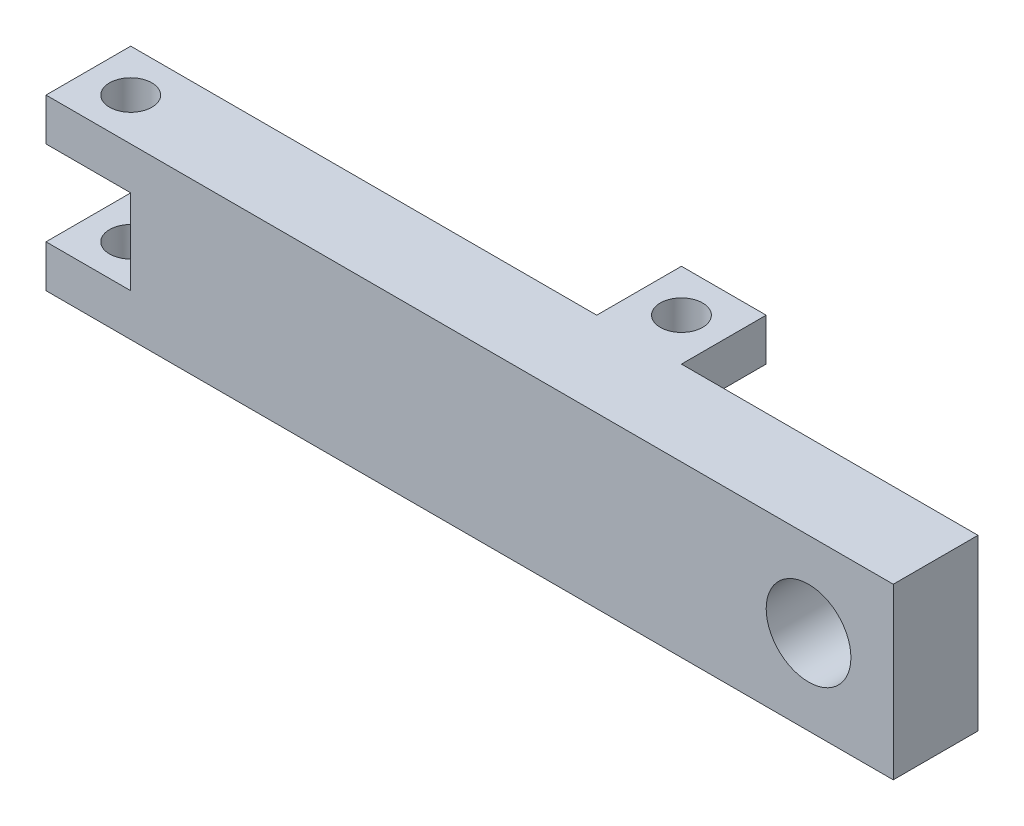
SolidWorks part; units mm, degrees
ref_plane "Front" through (0, 0, 0) normal (0, 0, 1) x (1, 0, 0)
ref_plane "Top" through (0, 0, 0) normal (0, 1, 0) x (1, 0, 0)
ref_plane "Right" through (0, 0, 0) normal (1, 0, 0) x (0, 0, -1)
sketch "Sketch1" plane through (0, 0, 0) normal (0, 1, 0) x (1, 0, 0)
  line L1 (-60, 5) -> (40, 5)
  line L2 (-60, 5) -> (-60, -5)
  line L3 (-60, -5) -> (40, -5)
  line L4 (40, 5) -> (40, -5)
  line L5 (-60, 5) -> (40, -5) construction
  line L6 (-60, -5) -> (40, 5) construction
  line L8 (-5, 15) -> (5, 15)
  line L9 (-5, 15) -> (-5, 5)
  line L10 (-5, 5) -> (5, 5)
  line L11 (5, 15) -> (5, 5)
  line L12 (-5, 15) -> (5, 5) construction
  line L13 (-5, 5) -> (5, 15) construction
  circle A0 centre (-55, 0) radius 2.5
  circle A2 centre (0, 10) radius 2.5
  point P0 (0, 10)
  point P1 (5, 0)
  point P15 (-10, 0)
  dimension "D3" = 5
  dimension "D5" = 10
  dimension "D8" = 5
  dimension "D1" = 10
  dimension "D2" = 100
  dimension "D4" = 5
  dimension "D6" = 55
  dimension "D7" = 10
  dimension "D9" = 55
extrude "Boss-Extrude1" add sketch "Sketch1" against normal blind 20 contours L4 L1 L2 L3 A0 | L11 L8 L9 L1 A2
sketch "Sketch2" plane through (-60, 0, 0) normal (-1, 0, 0) x (0, 0, 1)
  line L0 (5, -20) -> (5, 0) construction
  line L1 (-5, -5) -> (5, -5)
  line L2 (-5, -5) -> (-5, -15)
  line L3 (-5, -15) -> (5, -15)
  line L4 (5, -5) -> (5, -15)
  line L5 (-5, -5) -> (5, -15) construction
  line L6 (-5, -15) -> (5, -5) construction
  line L7 (-5, -20) -> (-5, 0) construction
  line L9 (5, -20) -> (5, 0) construction
  line L10 (-5, -20) -> (-5, 0) construction
  line L11 (-5, 0) -> (5, 0) construction
  point P0 (0, -10)
  dimension "D1" = 10
  dimension "D2" = 5
extrude "Cut-Extrude1" cut sketch "Sketch2" against normal blind 10
sketch "Sketch5" plane through (0, 0, -15) normal (0, 0, -1) x (-1, 0, 0)
  line L0 (-5, -20) -> (-5, 0) construction
  line L1 (-5, -5) -> (5, -5)
  line L2 (-5, -5) -> (-5, -15)
  line L3 (-5, -15) -> (5, -15)
  line L4 (5, -5) -> (5, -15)
  line L5 (5, -20) -> (5, 0) construction
  line L6 (5, 0) -> (-5, 0) construction
  dimension "D1" = 5
  dimension "D2" = 10
extrude "Cut-Extrude4" cut sketch "Sketch5" against normal up to surface (10 mm away) up to face at (22.5, -10, -5)
sketch "Sketch4" plane through (0, 0, -5) normal (0, 0, -1) x (-1, 0, 0)
  line L1 (-5, -20) -> (-40, -20) construction
  line L2 (-40, -20) -> (-40, 0) construction
  circle A0 centre (-30, -10) radius 5
  dimension "D1" = 10
  dimension "D2" = 10
  dimension "D3" = 10
extrude "Cut-Extrude3" cut sketch "Sketch4" against normal up to next
